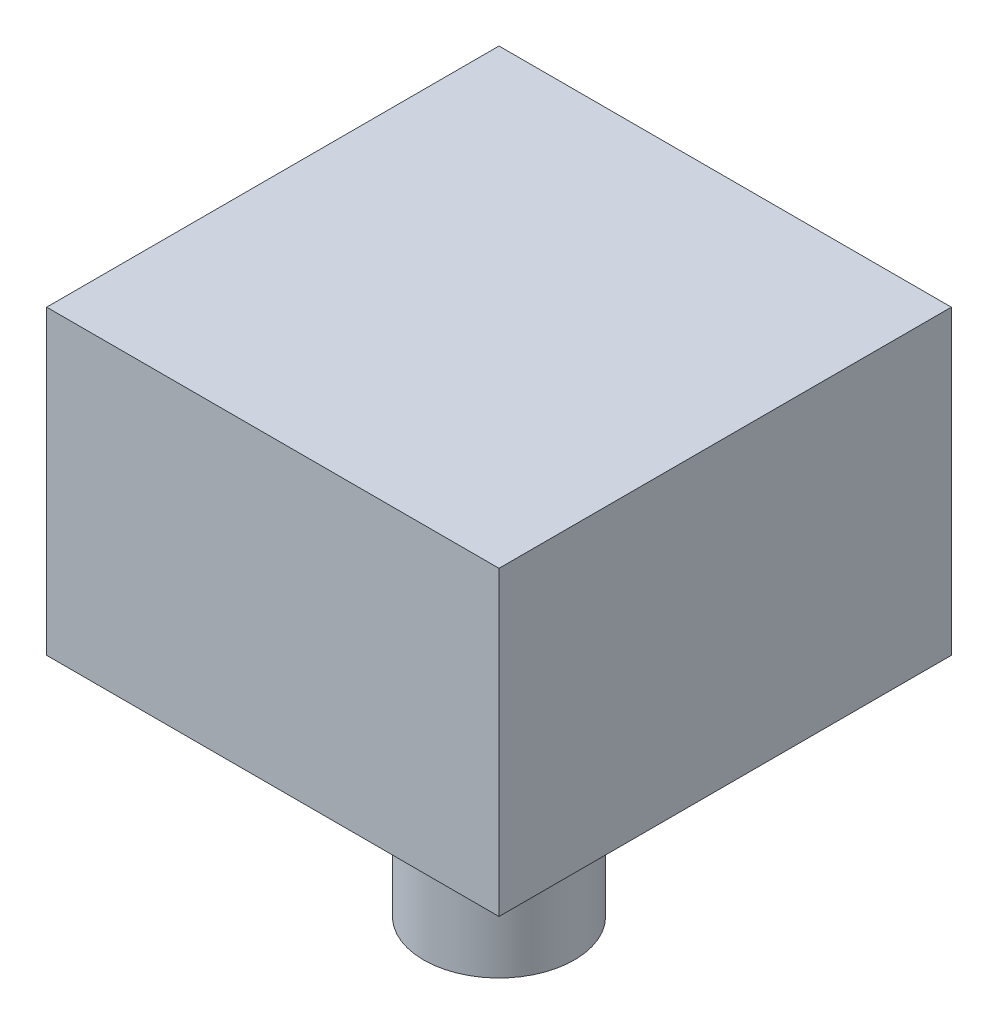
SolidWorks part; units mm, degrees
ref_plane "Plan de face" through (0, 0, 0) normal (0, 0, 1) x (1, 0, 0)
ref_plane "Plan de dessus" through (0, 0, 0) normal (0, 1, 0) x (1, 0, 0)
ref_plane "Plan de droite" through (0, 0, 0) normal (1, 0, 0) x (0, 0, -1)
sketch "Esquisse1" plane through (0, 0, 0) normal (0, 0, 1) x (1, 0, 0)
  line L1 (0, 0) -> (-30, 0)
  line L2 (0, 0) -> (0, 20)
  line L3 (0, 20) -> (-30, 20)
  line L4 (-30, 0) -> (-30, 20)
  dimension "D1" = 30
  dimension "D2" = 20
extrude "Boss.-Extru.1" add sketch "Esquisse1" along normal blind 30
sketch "Sketch1" plane through (0, 0, 0) normal (0, 1, 0) x (1, 0, 0)
  line L0 (-30, -30) -> (-30, 0) construction
  circle A0 centre (-20, -10) radius 5
  dimension "D1" = 10
  dimension "D2" = 10
  dimension "D3" = 10
extrude "Boss-Extrude1" add sketch "Sketch1" against normal blind 20
scale "Scale1" scale about centroid uniform scaling yes scale factor 0.6
